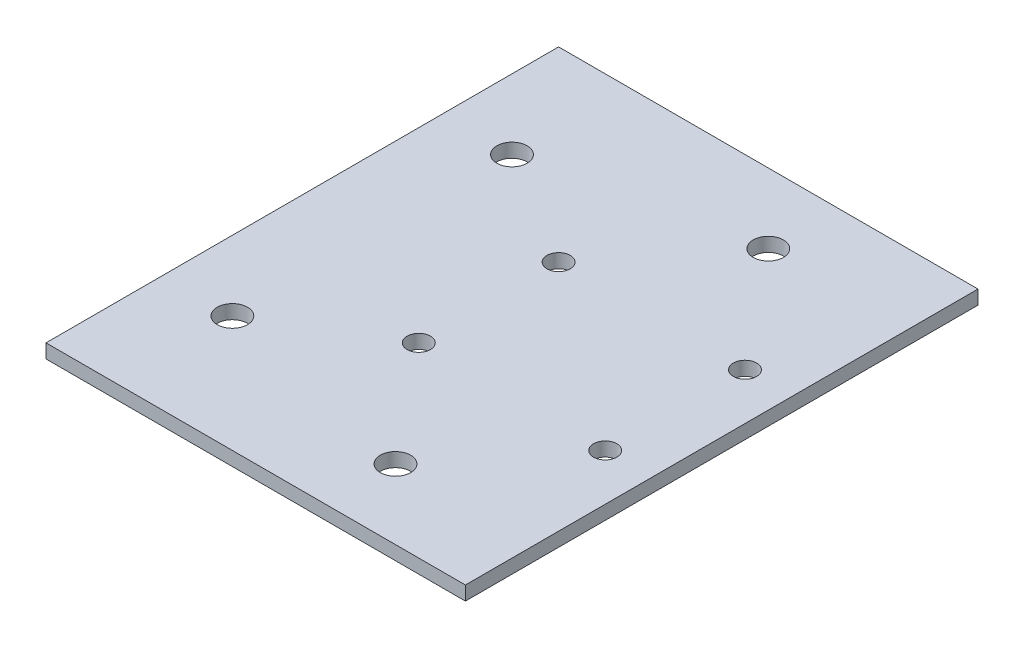
SolidWorks part; units mm, degrees
ref_plane "Front Plane" through (0, 0, 0) normal (0, 0, 1) x (1, 0, 0)
ref_plane "Top Plane" through (0, 0, 0) normal (0, 1, 0) x (1, 0, 0)
ref_plane "Right Plane" through (0, 0, 0) normal (1, 0, 0) x (0, 0, -1)
sketch "Sketch1" plane through (0, 0, 0) normal (0, 1, 0) x (1, 0, 0)
  line L0 (-15, 55) -> (-15, -55) construction
  line L1 (-45, 55) -> (45, 55)
  line L2 (-45, 55) -> (-45, -55)
  line L3 (-45, -55) -> (45, -55)
  line L4 (45, 55) -> (45, -55)
  line L5 (-45, 55) -> (45, -55) construction
  line L6 (-45, -55) -> (45, 55) construction
  line L7 (-5, 15) -> (35, 15) construction
  line L8 (-5, 15) -> (-5, -15) construction
  line L9 (-5, -15) -> (35, -15) construction
  line L10 (35, 15) -> (35, -15) construction
  line L11 (-5, 15) -> (35, -15) construction
  line L12 (-5, -15) -> (35, 15) construction
  circle A0 centre (-30, 30) radius 3.25
  circle A1 centre (-30, -30) radius 3.25
  circle A2 centre (-5, 15) radius 2.5
  circle A3 centre (35, 15) radius 2.5
  circle A4 centre (35, -15) radius 2.5
  circle A5 centre (-5, -15) radius 2.5
  circle A6 centre (15, -40) radius 3.25
  circle A7 centre (15, 40) radius 3.25
  point P0 (0, 0)
  point P11 (15, 0)
  point P23 (0, 0)
  dimension "D3" = 6.5
  dimension "D11" = 5
  dimension "D12" = 15
  dimension "D14" = 6.5
  dimension "D1" = 110
  dimension "D2" = 90
  dimension "D4" = 15
  dimension "D5" = 60
  dimension "D6" = 30
  dimension "D7" = 30
  dimension "D8" = 40
  dimension "D9" = 30
  dimension "D10" = 30
  dimension "D13" = 30
  dimension "D15" = 15
extrude "Boss-Extrude1" add sketch "Sketch1" along normal blind 3
